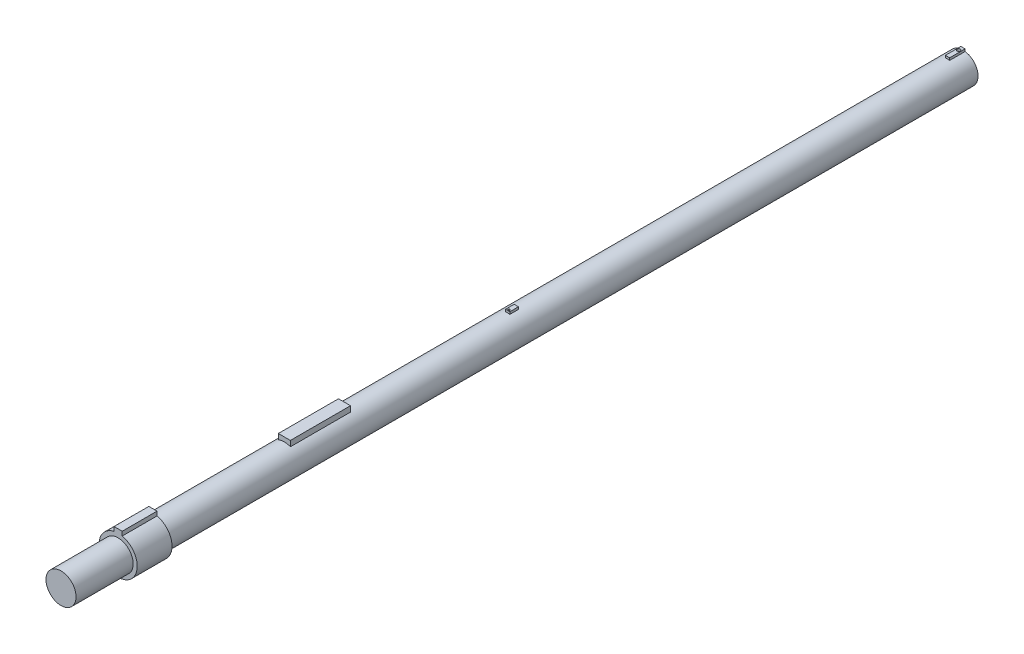
SolidWorks part; units mm, degrees
ref_plane "Front Plane" through (0, 0, 0) normal (0, 0, 1) x (1, 0, 0)
ref_plane "Top Plane" through (0, 0, 0) normal (0, 1, 0) x (1, 0, 0)
ref_plane "Right Plane" through (0, 0, 0) normal (1, 0, 0) x (0, 0, -1)
sketch "Sketch1" plane through (0, 0, 0) normal (0, 0, 1) x (1, 0, 0)
  circle A0 centre (0, 0) radius 17.5
extrude "Boss-Extrude1" add sketch "Sketch1" along normal blind 1050
ref_plane "Plane1" through (0, 0, 525) normal (0, 0, 1) x (1, 0, 0)
sketch "Sketch2" plane through (0, 0, 525) normal (0, 0, 1) x (1, 0, 0)
  line L0 (0, 17.5) -> (42.7293, 17.5) construction
  line L1 (0, 17.5) -> (0, 45) construction
  line L3 (-2.5, 15) -> (2.5, 15)
  line L4 (-2.5, 15) -> (-2.5, 20)
  line L5 (-2.5, 20) -> (2.5, 20)
  line L6 (2.5, 15) -> (2.5, 20)
  line L7 (-2.5, 15) -> (2.5, 20) construction
  line L8 (-2.5, 20) -> (2.5, 15) construction
  circle A0 centre (0, 0) radius 17.5 construction
  dimension "D1" = 5
  dimension "D2" = 5
extrude "Boss-Extrude2" add sketch "Sketch2" along normal blind 5 and the other way blind 5
sketch "Sketch5" plane through (0, 0, 1050) normal (0, 0, 1) x (1, 0, 0)
  circle A0 centre (0, 0) radius 17.5
  circle A1 centre (0, 0) radius 11.1125
  dimension "D1" = 22.225
extrude "Boss-Extrude3" add sketch "Sketch5" against normal blind 40.5005
ref_plane "Plane2" through (0, 0, 943) normal (0, 0, 1) x (1, 0, 0)
sketch "Sketch7" plane through (0, 0, 943) normal (0, 0, 1) x (1, 0, 0)
  circle A0 centre (0, 0) radius 22.225
  dimension "D1" = 44.45
extrude "Boss-Extrude4" add sketch "Sketch7" along normal blind 40.5005
sketch "Sketch11" plane through (0, 0, 983.5005) normal (0, 0, 1) x (1, 0, 0)
  line L0 (0, 0) -> (0, 17.855) construction
  line L2 (-4.765, 26.595) -> (4.765, 26.595)
  line L3 (-4.765, 26.595) -> (-4.765, 17.855)
  line L4 (-4.765, 17.855) -> (4.765, 17.855)
  line L5 (4.765, 26.595) -> (4.765, 17.855)
  point P1 (4.765, 22.225)
  dimension "D1" = 4.37
  dimension "D2" = 9.53
extrude "Boss-Extrude5" add sketch "Sketch11" against normal blind 40.5005 contours L2 L5 L4 L3
sketch "Sketch12" plane through (0, 0, 0) normal (0, 0, -1) x (-1, 0, 0)
  line L0 (0, 0) -> (0, 17.5) construction
  line L6 (2.5, 15) -> (-2.5, 15)
  line L7 (2.5, 15) -> (2.5, 20)
  line L8 (2.5, 20) -> (-2.5, 20)
  line L9 (-2.5, 15) -> (-2.5, 20)
  line L10 (2.5, 15) -> (-2.5, 20) construction
  line L11 (2.5, 20) -> (-2.5, 15) construction
  arc A0 (2.5, 17.3205) -> (-2.5, 17.3205) centre (0, 0) ccw construction
  dimension "D1" = 5
  dimension "D2" = 5
extrude "Boss-Extrude6" add sketch "Sketch12" against normal blind 18
sketch "Sketch13" plane through (0, 20, 0) normal (0, 1, 0) x (1, 0, 0)
  circle A0 centre (0, -5) radius 2
  dimension "D2" = 4
extrude "Cut-Extrude1" cut sketch "Sketch13" against normal blind 10
sketch "Sketch15" plane through (0, 20, 0) normal (0, 1, 0) x (1, 0, 0)
  line L0 (0, -530) -> (0, -528.5) construction
  line L1 (-2.5, -530) -> (2.5, -530) construction
  circle A0 centre (0, -528.5) radius 1
  dimension "D1" = 2
  dimension "D2" = 1.5
extrude "Cut-Extrude3" cut sketch "Sketch15" against normal blind 10
ref_plane "Plane3" through (0, 0, 790) normal (0, 0, 1) x (1, 0, 0)
sketch "Sketch16" plane through (0, 0, 790) normal (0, 0, 1) x (1, 0, 0)
  line L2 (7, 12.5) -> (-7, 12.5)
  line L3 (7, 12.5) -> (7, 22.5)
  line L4 (7, 22.5) -> (-7, 22.5)
  line L5 (-7, 12.5) -> (-7, 22.5)
  dimension "D1" = 14
  dimension "D2" = 10
extrude "Boss-Extrude7" add sketch "Sketch16" against normal blind 70
